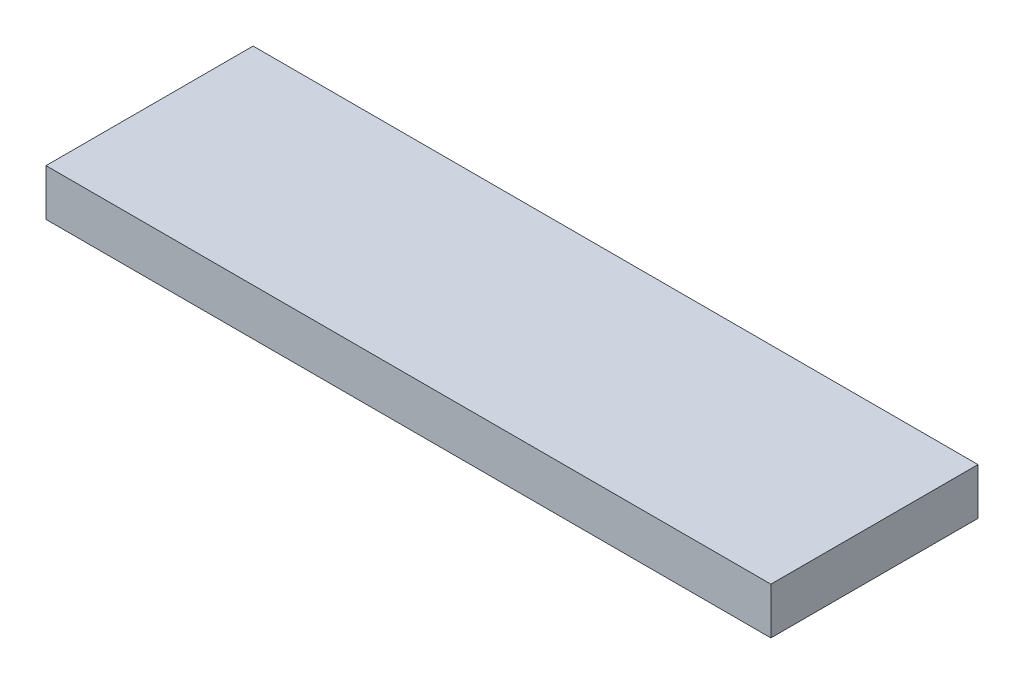
SolidWorks part; units mm, degrees
ref_plane "Front Plane" through (0, 0, 0) normal (0, 0, 1) x (1, 0, 0)
ref_plane "Top Plane" through (0, 0, 0) normal (0, 1, 0) x (1, 0, 0)
ref_plane "Right Plane" through (0, 0, 0) normal (1, 0, 0) x (0, 0, -1)
sketch "Sketch1" plane through (0, 0, 0) normal (0, 1, 0) x (1, 0, 0)
  line L1 (-35, 10) -> (35, 10)
  line L2 (-35, 10) -> (-35, -10)
  line L3 (-35, -10) -> (35, -10)
  line L4 (35, 10) -> (35, -10)
  line L5 (-35, 10) -> (35, -10) construction
  line L6 (-35, -10) -> (35, 10) construction
  point P0 (0, 0)
  dimension "D1" = 70
  dimension "D2" = 20
extrude "Boss-Extrude1" add sketch "Sketch1" along normal blind 4.5
